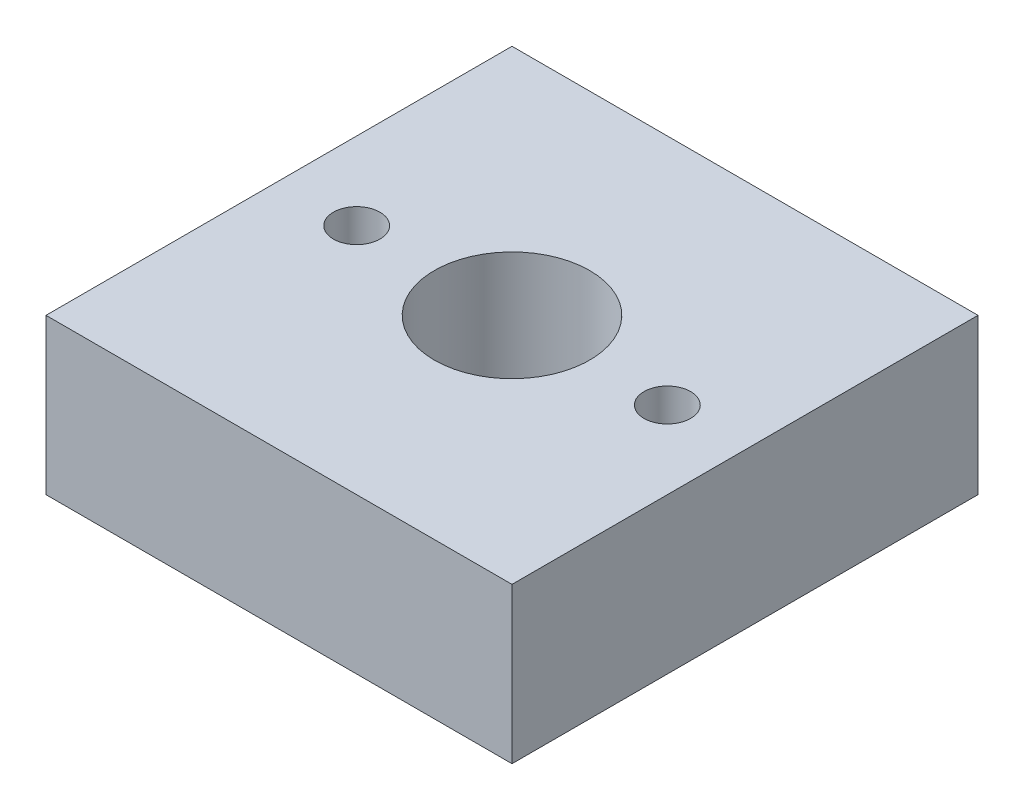
SolidWorks part; units mm, degrees
ref_plane "Płaszczyzna przednia" through (0, 0, 0) normal (0, 0, 1) x (1, 0, 0)
ref_plane "Płaszczyzna górna" through (0, 0, 0) normal (0, 1, 0) x (1, 0, 0)
ref_plane "Płaszczyzna prawa" through (0, 0, 0) normal (1, 0, 0) x (0, 0, -1)
sketch "Sketch1" plane through (0, 0, 0) normal (0, 1, 0) x (1, 0, 0)
  line L1 (0, 0) -> (30, 0)
  line L2 (0, 0) -> (0, 30)
  line L3 (0, 30) -> (30, 30)
  line L4 (30, 0) -> (30, 30)
  dimension "D1" = 30
  dimension "D2" = 30
extrude "Boss-Extrude1" add sketch "Sketch1" along normal blind 10
sketch "Sketch2" plane through (0, 10, 0) normal (0, 1, 0) x (1, 0, 0)
  line L0 (0, 0) -> (30, 30) construction
  line L1 (30, 0) -> (0, 30) construction
  circle A0 centre (15, 15) radius 5
  point P11 (15, 15)
  dimension "D1" = 10
extrude "Cut-Extrude1" cut sketch "Sketch2" against normal through all
hole_wizard "CSK for M3 Flat Head Machine Screw1" positions "Sketch3" profile "Sketch4" countersink size "M3" standard "ANSI Metric"
sketch "Sketch3" plane through (0, 10, 0) normal (0, 1, 0) x (1, 0, 0)
  line L0 (30, 30) -> (0, 30) construction
  line L1 (0, 30) -> (0, 0) construction
  line L2 (30, 0) -> (30, 30) construction
  point P0 (5, 15)
  point P2 (25, 15)
  dimension "D1" = 15
  dimension "D2" = 5
  dimension "D3" = 5
sketch "Sketch4" plane through (5, 10, -15) normal (1, 0, 0) x (0, 0, 1)
  line L0 (0, 0) -> (0, 10)
  line L1 (0, 10) -> (1.6, 10)
  line L2 (1.6, 10) -> (1.6, 1.55)
  line L3 (1.6, 1.55) -> (3.15, 0)
  line L5 (3.15, 0) -> (0, 0)
  line L6 (-1.6, 1.55) -> (-3.15, 0) construction
  line L11 (0, -6.35) -> (0, 107.95) construction
  dimension "Thru Hole Dia." = 3.2
  dimension "Thru Hole Depth" = 10
  dimension "Near C'Sink Dia." = 6.3
  dimension "Near C'Sink Angle" = 90
hole_wizard "Ø3.0mm Dowel Hole1" positions "Sketch5" profile "Sketch6" hole size "Ø3.0" standard "ANSI Metric" end condition through all
sketch "Sketch5" plane through (0, 10, 0) normal (0, 1, 0) x (1, 0, 0)
  line L0 (0, 30) -> (0, 0) construction
  line L1 (30, 0) -> (30, 30) construction
  line L2 (30, 30) -> (0, 30) construction
  point P0 (5, 15)
  point P2 (25, 15)
  point P5 (0, 0)
  dimension "D1" = 5
  dimension "D2" = 5
  dimension "D3" = 15
sketch "Sketch6" plane through (5, 10, -15) normal (1, 0, 0) x (0, 0, 1)
  line L0 (0, 0) -> (0, 10)
  line L1 (0, 10) -> (1.5, 10)
  line L2 (1.5, 10) -> (1.5, 0)
  line L5 (1.5, 0) -> (0, 0)
  line L11 (0, -6.35) -> (0, 107.95) construction
  dimension "Thru Hole Dia." = 3
  dimension "Thru Hole Depth" = 10
